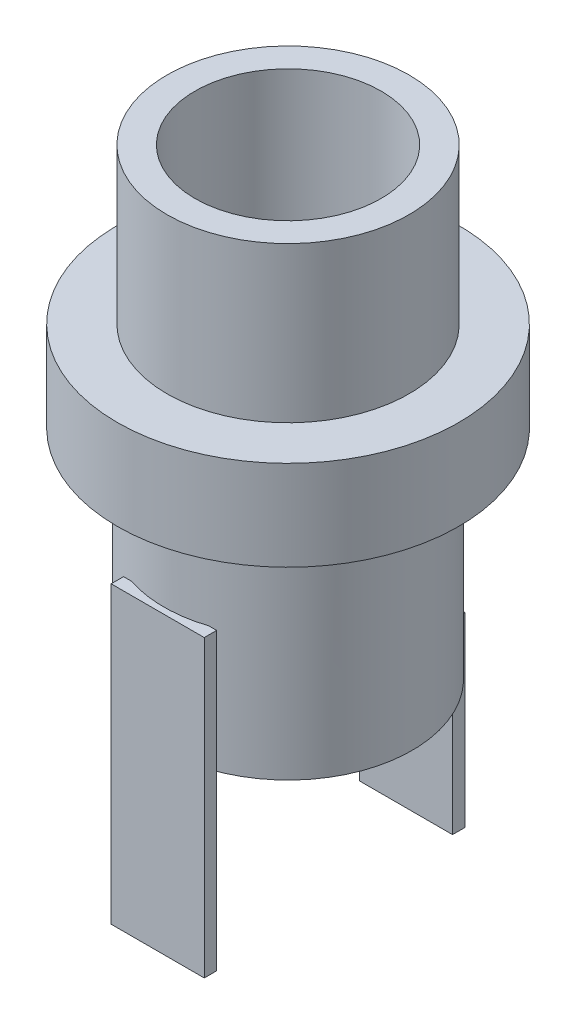
SolidWorks part; units mm, degrees
ref_plane "Piano frontale" through (0, 0, 0) normal (0, 0, 1) x (1, 0, 0)
ref_plane "Piano superiore" through (0, 0, 0) normal (0, 1, 0) x (1, 0, 0)
ref_plane "Piano destro" through (0, 0, 0) normal (1, 0, 0) x (0, 0, -1)
sketch "Schizzo1" plane through (0, 0, 0) normal (0, 1, 0) x (1, 0, 0)
  circle A0 centre (0, 0) radius 5.5
  dimension "D1" = 11
extrude "Estrusione-Estrusione1" add sketch "Schizzo1" along normal blind 2.9
sketch "Schizzo2" plane through (0, 2.9, 0) normal (0, 1, 0) x (1, 0, 0)
  circle A0 centre (0, 0) radius 3.9
  dimension "D1" = 7.8
extrude "Estrusione-Estrusione2" add sketch "Schizzo2" along normal blind 5
sketch "Schizzo3" plane through (0, 0, 0) normal (0, -1, 0) x (1, 0, 0)
  circle A0 centre (0, 0) radius 4
  dimension "D1" = 8
extrude "Estrusione-Estrusione3" add sketch "Schizzo3" along normal blind 7
sketch "Schizzo4" plane through (0, 7.9, 0) normal (0, 1, 0) x (1, 0, 0)
  circle A0 centre (0, 0) radius 3
  dimension "D1" = 6
extrude "Taglio-Estrusione1" cut sketch "Schizzo4" against normal blind 10
ref_plane "Piano1" through (-3.8, 0, 0) normal (1, 0, 0) x (0, 0, -1)
ref_plane "Piano2" through (0, 0, 3.8) normal (0, 0, 1) x (1, 0, 0)
ref_plane "Piano3" through (0, 0, -3.8) normal (0, 0, 1) x (1, 0, 0)
sketch "Schizzo5" plane through (0, 0, 3.8) normal (0, 0, 1) x (1, 0, 0)
  line L0 (-4, -7) -> (4, -7) construction
  line L1 (-1.5, -3) -> (1.5, -3)
  line L2 (-1.5, -3) -> (-1.5, -12.5)
  line L3 (-1.5, -12.5) -> (1.5, -12.5)
  line L4 (1.5, -3) -> (1.5, -12.5)
  line L5 (-4, 0) -> (4, 0) construction
  dimension "D1" = 5.5
  dimension "D2" = 3
  dimension "D3" = 3
  dimension "D4" = 1.5
extrude "Estrusione-Estrusione4" add sketch "Schizzo5" along normal blind 0.4
sketch "Schizzo7" plane through (-3.8, 0, 0) normal (1, 0, 0) x (0, 0, -1)
  line L0 (-3.8, -7) -> (4, -7) construction
  line L1 (1.5, -6.5) -> (-1.5, -6.5)
  line L2 (1.5, -6.5) -> (1.5, -12.5)
  line L3 (1.5, -12.5) -> (-1.5, -12.5)
  line L4 (-1.5, -6.5) -> (-1.5, -12.5)
  line L5 (-4.2, -12.5) -> (-3.8, -12.5) construction
  dimension "D1" = 3
  dimension "D2" = 1.5
  dimension "D3" = 0.5
extrude "Estrusione-Estrusione5" add sketch "Schizzo7" against normal blind 0.4
sketch "Schizzo8" plane through (0, 0, -3.8) normal (0, 0, 1) x (1, 0, 0)
  line L0 (-3.8, -7) -> (4, -7) construction
  line L1 (1.5, -6.5) -> (-1.5, -6.5)
  line L2 (1.5, -6.5) -> (1.5, -12.5)
  line L3 (1.5, -12.5) -> (-1.5, -12.5)
  line L4 (-1.5, -6.5) -> (-1.5, -12.5)
  line L6 (-4.2, -12.5) -> (-3.8, -12.5) construction
  dimension "D1" = 3
  dimension "D2" = 1.5
  dimension "D3" = 0.5
extrude "Estrusione-Estrusione6" add sketch "Schizzo8" against normal blind 0.4
